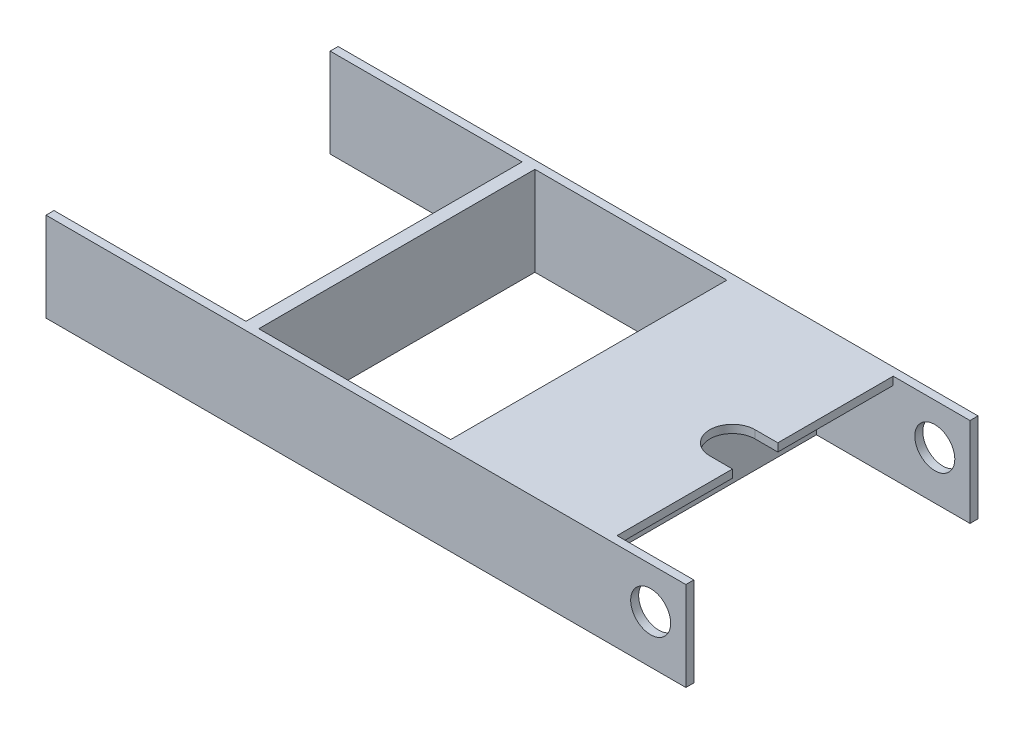
SolidWorks part; units mm, degrees
ref_plane "Front Plane" through (0, 0, 0) normal (0, 0, 1) x (1, 0, 0)
ref_plane "Top Plane" through (0, 0, 0) normal (0, 1, 0) x (1, 0, 0)
ref_plane "Right Plane" through (0, 0, 0) normal (1, 0, 0) x (0, 0, -1)
sketch "Sketch1" plane through (0, 0, 0) normal (0, 1, 0) x (1, 0, 0)
  line L1 (63.5, 28.9941) -> (-63.5, 28.9941)
  line L2 (63.5, 28.9941) -> (63.5, -28.9941)
  line L3 (63.5, -28.9941) -> (-63.5, -28.9941)
  line L4 (-63.5, 28.9941) -> (-63.5, -28.9941)
  line L5 (63.5, 28.9941) -> (-63.5, -28.9941) construction
  line L6 (63.5, -28.9941) -> (-63.5, 28.9941) construction
  point P0 (0, 0)
  dimension "D1" = 127
  dimension "D2" = 57.9882
extrude "Boss-Extrude1" add sketch "Sketch1" along normal blind 17.7013
sketch "Sketch2" plane through (0, 17.7013, 0) normal (0, 1, 0) x (1, 0, 0)
  line L0 (48.26, 28.9941) -> (48.26, -28.9941)
  line L1 (63.5, 28.9941) -> (-63.5, 28.9941) construction
  line L2 (-63.5, -28.9941) -> (63.5, -28.9941) construction
  line L3 (-63.5, 28.9941) -> (-63.5, -28.9941) construction
  line L4 (48.26, 27.4066) -> (63.5, 27.4066)
  line L5 (63.5, -28.9941) -> (63.5, 28.9941) construction
  line L6 (48.26, -27.4066) -> (63.5, -27.4066)
  line M6 (63.5, -28.9941) -> (63.5, 28.9941)
  dimension "D1" = 111.76
  dimension "D2" = 1.5875
  dimension "D3" = 1.5875
extrude "Cut-Extrude1" cut sketch "Sketch2" against normal through all contours L0 L6 L4 M6
sketch "Sketch3" plane through (0, 0, -27.4066) normal (0, 0, 1) x (1, 0, 0)
  line L0 (63.5, 0) -> (63.5, 17.7013) construction
  line L1 (48.26, 17.7013) -> (63.5, 17.7013) construction
  circle A0 centre (56.515, 9.5479) radius 3.9687
  dimension "D1" = 7.9375
  dimension "D2" = 6.985
  dimension "D3" = 8.1534
extrude "Cut-Extrude2" cut sketch "Sketch3" against normal through all both and the other way through all
sketch "Sketch4" plane through (0, 17.7013, 0) normal (0, 1, 0) x (1, 0, 0)
  line L0 (48.26, 27.4066) -> (48.26, -27.4066) construction
  line L1 (0, 0) -> (50000, 0) construction
  line L3 (43.76, 4.5) -> (48.26, 4.5)
  line L4 (43.76, -4.5) -> (48.26, -4.5)
  circle A0 centre (43.76, 0) radius 4.5
  line M10 (48.26, -27.4066) -> (48.26, 27.4066)
  dimension "D1" = 9
sketch "Sketch6" plane through (48.26, 0, 0) normal (1, 0, 0) x (0, 0, -1)
  line L0 (-27.4066, 16.1138) -> (27.4066, 16.1138)
  line L1 (-27.4066, 0) -> (-27.4066, 17.7013) construction
  line L2 (27.4066, 0) -> (27.4066, 17.7013) construction
  line L3 (27.4066, 17.7013) -> (-27.4066, 17.7013) construction
  line M3 (-27.4066, 17.7013) -> (-27.4066, 0)
  line M4 (-27.4066, 0) -> (27.4066, 0)
  line M5 (27.4066, 0) -> (27.4066, 17.7013)
  dimension "D1" = 1.5875
extrude "Cut-Extrude5" cut sketch "Sketch6" against normal blind 15.24 and the other way through all contours L0 M3 M4 M5
extrude "Cut-Extrude6" cut sketch "Sketch4" against normal through all contours A0 L1 | A0 L3 M10 | L1 A0 | A0 L4 M10
sketch "Sketch7" plane through (0, 17.7013, 0) normal (0, 1, 0) x (1, 0, 0)
  line L0 (48.26, 27.4066) -> (-63.5, 27.4066)
  line L1 (-63.5, 28.9941) -> (-63.5, -28.9941) construction
  line L2 (48.26, -27.4066) -> (-63.5, -27.4066)
  line L3 (-25.4, 27.4066) -> (-25.4, -27.4066)
  line M8 (-63.5, 28.9941) -> (-63.5, -28.9941)
  dimension "D1" = 38.1
extrude "Cut-Extrude7" cut sketch "Sketch7" against normal through all contours L3 L0 L2 M8
sketch "Sketch8" plane through (0, 17.7013, 0) normal (0, 1, 0) x (1, 0, 0)
  line L0 (-25.4, 27.4066) -> (48.26, 27.4066)
  line L1 (-25.4, -27.4066) -> (48.26, -27.4066)
  line L2 (-22.86, 27.4066) -> (-22.86, -27.4066)
  line L3 (15.24, 27.4066) -> (15.24, -27.4066)
  line L4 (-25.4, 27.4066) -> (-25.4, -27.4066) construction
  dimension "D1" = 2.54
  dimension "D2" = 38.1
extrude "Cut-Extrude8" cut sketch "Sketch8" against normal through all contours L3 L0 L2 L1
